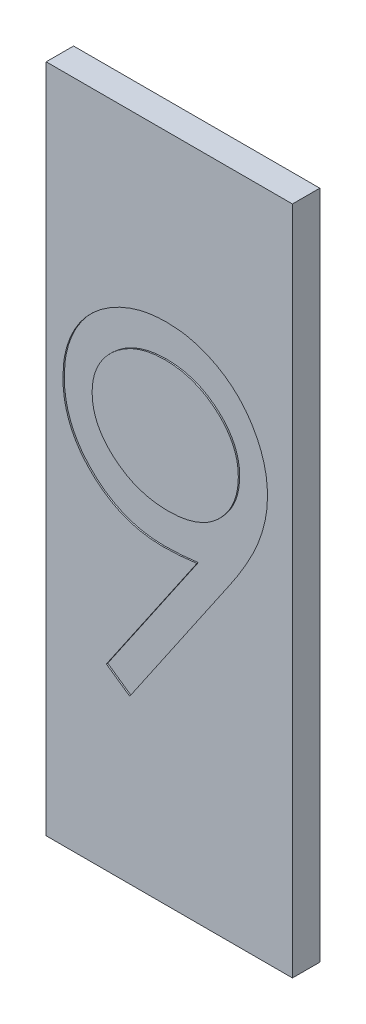
SolidWorks part; units mm, degrees
ref_plane "正面" through (0, 0, 0) normal (0, 0, 1) x (1, 0, 0)
ref_plane "平面" through (0, 0, 0) normal (0, 1, 0) x (1, 0, 0)
ref_plane "右側面" through (0, 0, 0) normal (1, 0, 0) x (0, 0, -1)
sketch "ｽｹｯﾁ1" plane through (0, 0, 0) normal (0, 0, 1) x (1, 0, 0)
  line L0 (18, 0) -> (0, 0)
  line L1 (18, 49) -> (0, 49)
  line L2 (0, 0) -> (0, 49)
  line L4 (18, 0) -> (18, 49)
extrude "ﾎﾞｽ - 押し出し1" add sketch "ｽｹｯﾁ1" along normal blind 2
sketch "ｽｹｯﾁ2" plane through (0, 0, 2) normal (0, 0, 1) x (1, 0, 0)
  text T0 "9" font "Century Gothic" height in points 90
extrude "ｶｯﾄ - 押し出し1" cut sketch "ｽｹｯﾁ2" against normal blind 0.1
